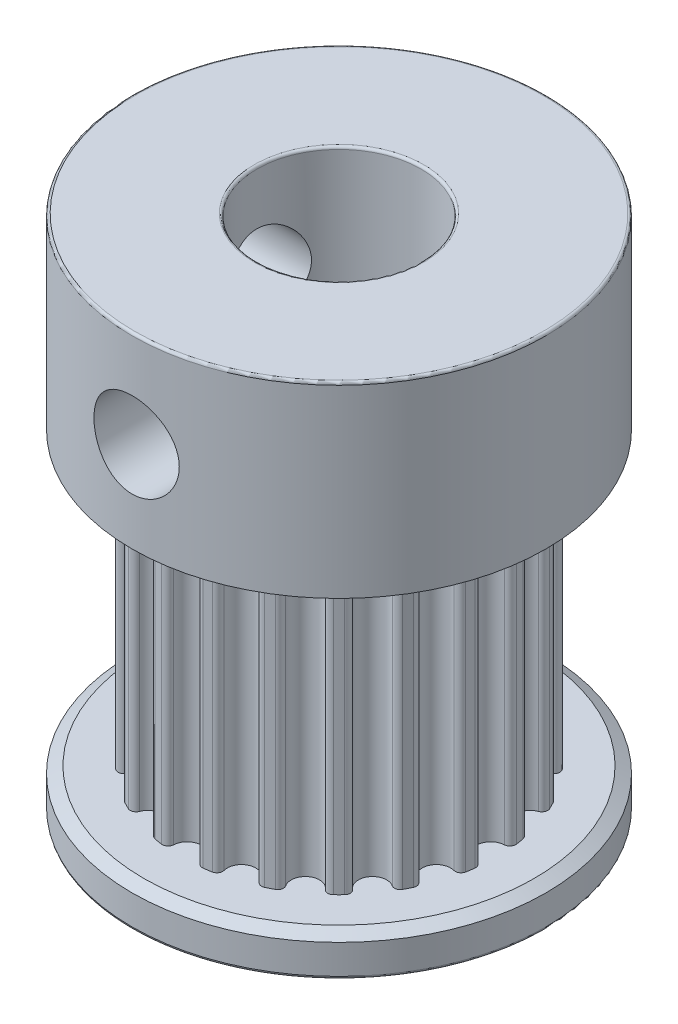
SolidWorks part; units mm, degrees
ref_plane "Front Plane" through (0, 0, 0) normal (0, 0, 1) x (1, 0, 0)
ref_plane "Top Plane" through (0, 0, 0) normal (0, 1, 0) x (1, 0, 0)
ref_plane "Right Plane" through (0, 0, 0) normal (1, 0, 0) x (0, 0, -1)
sketch "Sketch1" plane through (0, 0, 0) normal (0, 0, 1) x (1, 0, 0)
  line L0 (0, 0) -> (0, 21) construction
  line L2 (3.175, 0) -> (3.175, 20)
  line L3 (3.175, 20) -> (8, 20)
  line L5 (3.175, 0) -> (8, 0)
  line L6 (8, 0) -> (8, 1.5)
  line L7 (8, 1.5) -> (6.11, 1.5)
  line L8 (6.11, 1.5) -> (6.11, 12.5)
  line L9 (6.11, 12.5) -> (8, 12.5)
  line L10 (8, 12.5) -> (8, 20)
  point P3 (3.3734, 0)
  point P5 (0, 0)
  point P7 (0, 0)
  point P8 (12.8, 13.3345)
  point P15 (12.8, 21.5)
  point P16 (0, 21)
  point P17 (11.15, 21.5)
  point P18 (0, 0)
  point P19 (12.5334, 21.5)
  dimension "D1" = 1.5
  dimension "D2" = 11
  dimension "D3" = 6.11
  dimension "D4" = 8
  dimension "D5" = 7.5
  dimension "D6" = 3.175
  dimension "D7" = 20
revolve "Revolve1" add sketch "Sketch1" angle 360 about L0
sketch "Sketch2" plane through (0, 1.5, 0) normal (0, 1, 0) x (1, 0, 0)
  line L0 (0, 0) -> (0, 6.42) construction
  line L1 (-0.9558, 6.0348) -> (-1.0043, 6.341)
  line L2 (0.9558, 6.0348) -> (1.0043, 6.341)
  line L3 (0, 0) -> (-0.9558, 6.0348) construction
  line L4 (0, 0) -> (0.9558, 6.0348) construction
  circle A0 centre (0, 0) radius 6.11 construction
  circle A1 centre (0, 0) radius 6.11 construction
  arc A4 (-0.5494, 5.8442) -> (0.5494, 5.8442) centre (0, 5.87) ccw
  circle A5 centre (0, 0) radius 5.87 construction
  arc A8 (-1.0043, 6.341) -> (1.0043, 6.341) centre (0, 0) cw
  circle A9 centre (0, 0) radius 6.42 construction
  arc A10 (-0.8039, 6.0569) -> (-0.9558, 6.0348) centre (0, 0) ccw
  circle A12 centre (0, 5.87) radius 0.55 construction
  arc A13 (-0.5494, 5.8442) -> (-0.8039, 6.0569) centre (-0.7743, 5.8337) ccw
  arc A14 (0.8039, 6.0569) -> (0.9558, 6.0348) centre (0, 0) cw
  arc A15 (0.5494, 5.8442) -> (0.8039, 6.0569) centre (0.7743, 5.8337) cw
  point P12 (0, 5.87)
  point P19 (0, 5.2432)
  point P22 (0, 0)
  point P25 (0, 5.32)
  point P26 (0, 6.11)
  point P28 (0, 0)
  point P29 (0, 0)
  point P30 (0, 0)
  dimension "D5" = 12.84
  dimension "D6" = 1.1
  dimension "D4" = 18
extrude "Cut-Extrude1" cut sketch "Sketch2" along normal up to surface (11 mm away) up to face at (0, 12.5, -8)
pattern_circular "CirPattern1" count 20 over 360 about axis through (0, 0, 0) along (0, 1, 0) of "Cut-Extrude1"
chamfer "Chamfer1" distance 0.45 angle 30 2 edges at (0, 12.5, -8) (0, 1.5, -8)
fillet "Fillet1" radius 0.1 4 edges at (0, 0, -3.175) (0, 20, -3.175) (0, 20, -8) (0, 0, -8)
sketch "Sketch5" plane through (0, 0, 0) normal (0, 0, 1) x (1, 0, 0)
  line L0 (0, 20) -> (0, 12.5) construction
  line L1 (3.275, 20) -> (-3.275, 20) construction
  line L2 (-0.5494, 12.5) -> (0.5494, 12.5) construction
  point P6 (0, 16.25)
hole_wizard "M4 Tapped Hole2" positions "3DSketch2" profile "Sketch6" tap size "M4" standard "ISO"
sketch3d "3DSketch2"
  point P0 (0, 16.25, 0)
  point P3 (0, 16.25, 8)
  point P6 (0.5082, 15.9428, 7.9838)
  point P7 (0, 0, 0)
sketch "Sketch6" plane through (0, 16.25, 8) normal (1, 0, 0) x (0, -1, 0)
  line L0 (0, 0) -> (0, 6.5)
  line L1 (0, 6.5) -> (1.65, 5.5086)
  line L2 (1.65, 5.5086) -> (1.65, 0)
  line L5 (1.65, 0) -> (0, 0)
  line L10 (0, 6.5) -> (-1.65, 5.5086) construction
  line L11 (0, -6.35) -> (0, 107.95) construction
  dimension "Tap Drill Dia." = 3.3
  dimension "Tap Drill Depth" = 6.5
  dimension "Drill Angle" = 118
cosmetic thread "Hole Thread2" parameters "D1"=5.3, "D2"=4
cosmetic thread "Hole Thread6" parameters "D1"=5.3, "D2"=4
pattern_circular "CirPattern2" count 2 over 90 about axis through (0, 19.9, 0) along (0, 1, 0) of "M4 Tapped Hole2"
cosmetic thread "Hole Thread4" parameters "D1"=5.3, "D2"=4
cosmetic thread "Hole Thread7" parameters "D1"=5.2874, "D2"=4
